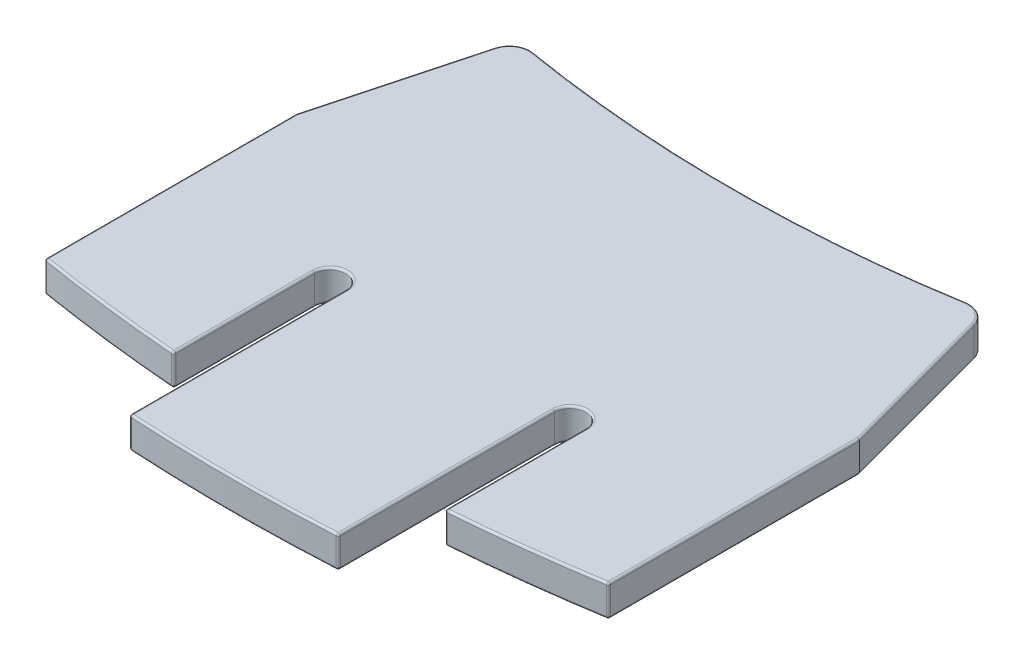
SolidWorks part; units mm, degrees
ref_plane "Front Plane" through (0, 0, 0) normal (0, 0, 1) x (1, 0, 0)
ref_plane "Top Plane" through (0, 0, 0) normal (0, 1, 0) x (1, 0, 0)
ref_plane "Right Plane" through (0, 0, 0) normal (1, 0, 0) x (0, 0, -1)
sketch "Sketch1" plane through (0, 0, 0) normal (0, 1, 0) x (1, 0, 0)
  line L1 (-10, 29) -> (-10, 8.2859)
  line L2 (-13, 28.9943) -> (-13, 15.5037)
  line L3 (27, 0.004) -> (-27, 0.004) construction
  line L4 (-27, 17.1838) -> (-27, 41.2148)
  line L5 (0, 0) -> (0, 56) construction
  line L6 (22.9726, 56.2452) -> (27, 41.2148)
  line L7 (-22.9726, 56.2452) -> (-27, 41.2148)
  line L8 (27, 17.1838) -> (27, 41.2148)
  line L10 (10, 29) -> (10, 8.2859)
  line L11 (13, 29) -> (13, 15.5037)
  arc A0 (-10, 29) -> (-13, 28.9943) centre (-11.5, 29) ccw
  arc A1 (13, 15.5037) -> (27, 17.1838) centre (0, 183) ccw
  arc A3 (-20.7146, 57.7007) -> (20.7146, 57.7007) centre (0, 183) ccw
  arc A5 (-22.9726, 56.2452) -> (-20.7146, 57.7007) centre (-21.0408, 55.7275) cw
  arc A6 (22.9726, 56.2452) -> (20.7146, 57.7007) centre (21.0408, 55.7275) ccw
  arc A8 (10, 29) -> (13, 29) centre (11.5, 29) cw
  arc A10 (-10, 8.2859) -> (10, 8.2859) centre (0, 183) ccw
  arc A11 (-27, 17.1838) -> (-13, 15.5037) centre (0, 183) ccw
  point P20 (-22.5, 58.009)
  point P29 (22.5, 58.009)
  dimension "D9" = 350
  dimension "D7" = 22.5
  dimension "D10" = 1.5
  dimension "D3" = 183
  dimension "D5" = 127
  dimension "D8" = 168
  dimension "D13" = 1.5
  dimension "D14" = 56
  dimension "D4" = 168
  dimension "D17" = 2
  dimension "D1" = 3
  dimension "D2" = 10
  dimension "D6" = 15
  dimension "D11" = 27
  dimension "D12" = 3
  dimension "D15" = 27
  dimension "D16" = 10
extrude "Boss-Extrude1" add sketch "Sketch1" along normal blind 3
fillet "Fillet1" radius 0.2 38 edges at (13, 0, -22.2519) (13, 3, -22.2519) (10, 0, -18.643) (10, 3, -18.643) (11.5, 0, -30.5) (11.5, 3, -30.5) (27, 0, -29.1993) (27, 3, -29.1993) (24.9863, 0, -48.73) (24.9863, 3, -48.73) (22.1244, 0, -57.4085) (22.1244, 3, -57.4085) (0, 0, -56) (0, 3, -56) (-22.1244, 0, -57.4085) (-22.1244, 3, -57.4085) (-24.9863, 0, -48.73) (-24.9863, 3, -48.73) (-27, 0, -29.1993) (-27, 3, -29.1993) (-10, 0, -18.643) (-10, 3, -18.643) (-13, 0, -22.249) (-13, 3, -22.249) (-11.5028, 0, -30.5) (-11.5028, 3, -30.5) (0, 0, -8) (20.0176, 0, -16.1968) (-20.0176, 0, -16.1968) (-20.0176, 3, -16.1968) (20.0176, 3, -16.1968) (0, 3, -8) (13, 1.5, -15.5037) (-13, 1.5, -15.5037) (-27, 1.5, -17.1838) (27, 1.5, -17.1838) (-10, 1.5, -8.2859) (10, 1.5, -8.2859)
ref_plane "Plane1" through (0, 0, -28.9943) normal (0, 0, 1) x (0, -1, 0)
ref_plane "Plane2" through (0, 0, -28.9943) normal (0, 0, 1) x (0, -1, 0)
